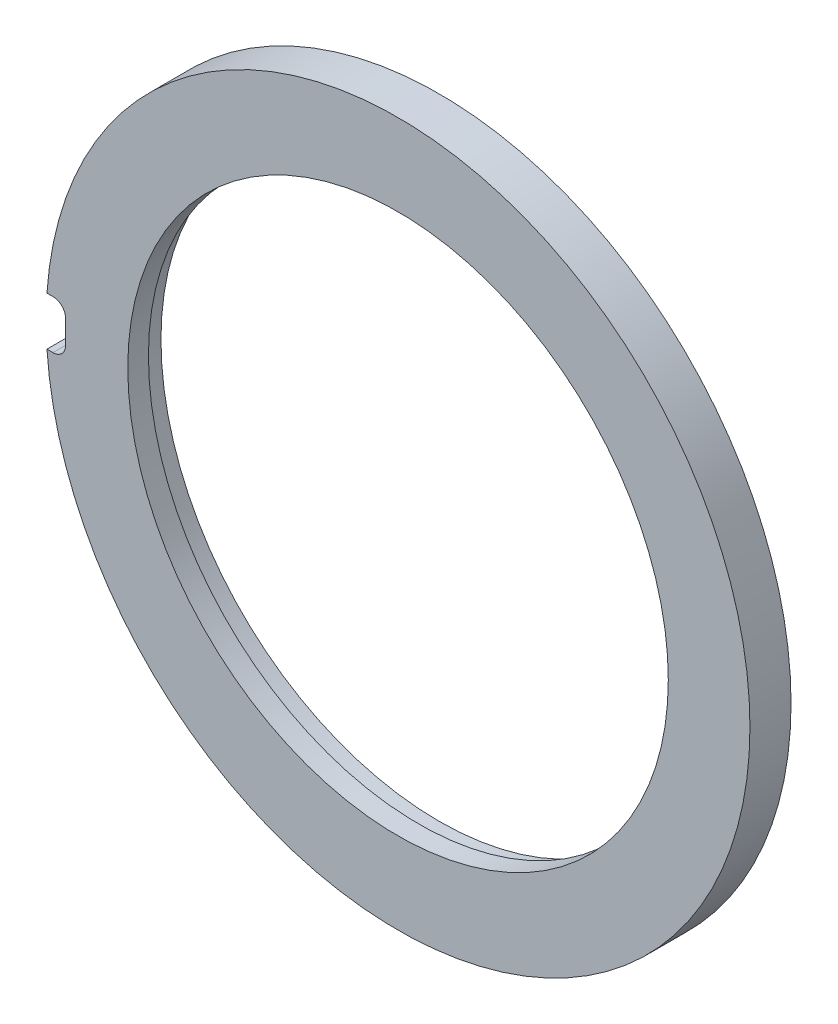
SolidWorks part; units mm, degrees
material "Латунь ЛС59-1Т ГОСТ 15527-2004"
ref_plane "Спереди" through (0, 0, 0) normal (0, 0, 1) x (1, 0, 0)
ref_plane "Сверху" through (0, 0, 0) normal (0, 1, 0) x (1, 0, 0)
ref_plane "Справа" through (0, 0, 0) normal (1, 0, 0) x (0, 0, -1)
sketch "Эскиз1" plane through (0, 0, 0) normal (0, 1, 0) x (1, 0, 0)
  line L0 (0, 0) -> (0, 27.5293) construction
  line L1 (-16.7, 0) -> (-12.825, 0)
  line L2 (-16.7, 0) -> (-16.7, 1.95)
  line L3 (-16.7, 1.95) -> (-13.2, 1.95)
  line L4 (-12.825, 0) -> (-12.825, 0.98)
  line L5 (-13.2, 1.95) -> (-13.2, 0.98)
  line L6 (-13.2, 0.98) -> (-12.825, 0.98)
  dimension "D1" = 25.65
  dimension "D2" = 33.4
  dimension "D3" = 26.4
  dimension "D4" = 0.98
  dimension "D5" = 0.97
revolve "Повернуть1" add sketch "Эскиз1" angle 360 about L0
sketch "Эскиз2" plane through (0, 0, -1.95) normal (0, 0, -1) x (-1, 0, 0)
  line L0 (0, 0) -> (15.7736, 0) construction
  line L2 (16.6604, 1.15) -> (15.7736, 1.15)
  line L3 (15.7736, 1.15) -> (15.7736, -1.15)
  line L4 (16.6604, -1.15) -> (15.7736, -1.15)
  circle A0 centre (0, 0) radius 16.7 construction
  arc A1 (16.6604, 1.15) -> (16.6604, -1.15) centre (13.2845, 0) cw
  dimension "D1" = 15.7736
  dimension "D2" = 2.3
extrude "Вырез-Вытянуть1" cut sketch "Эскиз2" against normal blind 3
sketch "Эскиз6" plane through (0, 0, 0) normal (0, 0, 1) x (1, 0, 0)
  circle A0 centre (-4.036, 11.088) radius 1.425
  circle A1 centre (5.54, -10.419) radius 1.425
  dimension "D1" = 2.85
extrude "Вырез-Вытянуть5" [suppressed] cut sketch "Эскиз6" against normal blind 0.33
fillet "Скругление2" radius 0.6 2 edges at (-15.7736, -1.15, -0.975) (-15.7736, 1.15, -0.975)
fillet "Скругление4" [suppressed] radius 1
sketch "Эскиз13" plane through (0, 0, 0) normal (0, 0, 1) x (1, 0, 0)
  line L0 (0, 0) -> (-9.6432, 10.7476) construction
  line L1 (-9.6432, 10.7476) -> (-14.2955, 2.0346) construction
  line L2 (-14.2955, 2.0346) -> (0, 0) construction
  line L3 (0, 0) -> (3.5861, 13.9872) construction
  line L4 (-6.3037, -12.9909) -> (0, 0) construction
  line L5 (0, 0) -> (-13.1793, -5.8997) construction
  line L6 (0, 0) -> (0, 21.7235) construction
  arc A0 (-9.6432, 10.7476) -> (-14.2955, 2.0346) centre (0, 0) ccw construction
  arc A1 (-13.1793, -5.8997) -> (-6.3037, -12.9909) centre (0, 0) ccw construction
  text T0 "METAL" font "Calibri" height 1.4
  text T1 "DRACULA" font "Calibri" height 1.4
sketch_block_instance "Блок1-2"
sketch_block "Блок1" parameters "D2"=14.4396, "D1"=14.9694, "D3"=14.2654, "D4"=14.2686, "D5"=21.7235
sketch "Эскиз16" plane through (0, 0, -1.95) normal (0, 0, -1) x (-1, 0, 0)
  arc A2 (16.6604, 1.15) -> (16.6604, -1.15) centre (0, 0) ccw
  circle A3 centre (0, 0) radius 16.7
  dimension "D1" = 0
sketch "Эскиз17" plane through (0, 0, -1.95) normal (0, 0, -1) x (-1, 0, 0)
  arc A2 (12.825, 0) -> (12.825, 0) centre (0, 0) ccw
  circle A3 centre (0, 0) radius 12.825
  dimension "D1" = 0
other "Переместить грань2" [suppressed] parameters "D1"=0.02
other "Переместить грань4" [suppressed] parameters "D1"=0.03
sketch "Эскиз29" [suppressed] plane through (0, 0, 0) normal (0, 0, 1) x (1, 0, 0)
  line L0 (0, 0) -> (14.4375, -3.1163) construction
  line L1 (0, 0) -> (11.6476, -9.5529) construction
  line L11 (0, 0) -> (11.3004, 16.4564) construction
  line L192 (0, 0) -> (19.6209, -1.551) construction
  arc A1 (13.8266, -2.9844) -> (10.937, -8.9701) centre (0, 0) cw construction
  arc A3 (15.2973, -1.2093) -> (8.6864, 12.6497) centre (0, 0) ccw construction
  arc A6 (14.101, -1.1147) -> (8.0071, 11.6605) centre (0, 0) ccw construction
  text T0 "КОЛОБОК" font "Vezitsa" height 1.2
  dimension "D3" = 1.2
extrude "Вырез-Вытянуть17" [suppressed] cut sketch "Эскиз29" against normal blind 0.2
